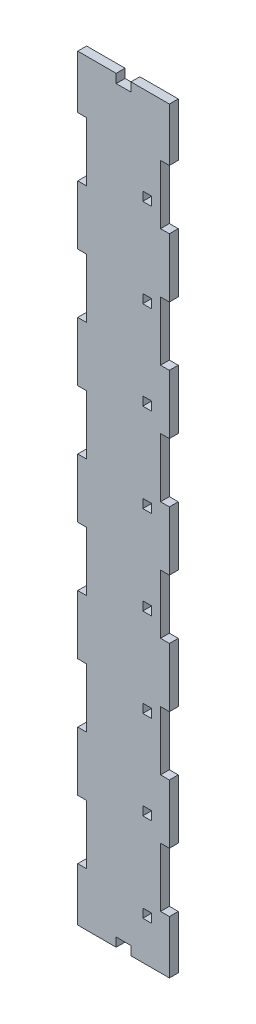
SolidWorks part; units mm, degrees
ref_plane "Front Plane" through (0, 0, 0) normal (0, 0, 1) x (1, 0, 0)
ref_plane "Top Plane" through (0, 0, 0) normal (0, 1, 0) x (1, 0, 0)
ref_plane "Right Plane" through (0, 0, 0) normal (1, 0, 0) x (0, 0, -1)
sketch "Эскиз2" plane through (0, 0, 0) normal (0, 0, 1) x (1, 0, 0)
  line L0 (-118.1292, 271.6721) -> (-110.4161, 271.6721)
  line L1 (-110.4161, 271.6721) -> (-110.4161, 276.0661)
  line L2 (-110.4161, 276.0661) -> (-86.722, 276.0661)
  line L3 (-86.722, 276.0661) -> (-86.722, 271.6721)
  line L4 (-86.722, 271.6721) -> (-64.5567, 271.6721)
  line L5 (-64.5567, 271.6721) -> (-64.5567, 276.0661)
  line L6 (-64.5567, 276.0661) -> (-40.8626, 276.0661)
  line L7 (-40.8626, 276.0661) -> (-40.8626, 271.6721)
  line L8 (-40.8626, 271.6721) -> (-10.2897, 271.6721)
  line L9 (-10.2897, 271.6721) -> (-10.2897, 248.237)
  line L10 (-10.2897, 248.237) -> (-4.5573, 248.237)
  line L11 (-4.5573, 248.237) -> (-4.5573, 230.0748)
  line L12 (-4.5573, 230.0748) -> (-10.2897, 230.0748)
  line L13 (-10.2897, 230.0748) -> (-10.2897, 213.0843)
  line L14 (-10.2897, 213.0843) -> (-4.5573, 213.0843)
  line L15 (-4.5573, 213.0843) -> (-4.5573, 194.9221)
  line L16 (-4.5573, 194.9221) -> (-10.2897, 194.9221)
  line L17 (-10.2897, 194.9221) -> (-10.2897, 177.9317)
  line L18 (-10.2897, 177.9317) -> (-4.5573, 177.9317)
  line L19 (-4.5573, 177.9317) -> (-4.5573, 159.7695)
  line L20 (-4.5573, 159.7695) -> (-10.2897, 159.7695)
  line L21 (-10.2897, 159.7695) -> (-10.2897, 142.7791)
  line L22 (-10.2897, 142.7791) -> (-4.5573, 142.7791)
  line L23 (-4.5573, 142.7791) -> (-4.5573, 124.6169)
  line L24 (-4.5573, 124.6169) -> (-10.2897, 124.6169)
  line L25 (-10.2897, 124.6169) -> (-10.2897, 107.6264)
  line L26 (-10.2897, 107.6264) -> (-4.5573, 107.6264)
  line L27 (-4.5573, 107.6264) -> (-4.5573, 89.4642)
  line L28 (-4.5573, 89.4642) -> (-10.2897, 89.4642)
  line L29 (-10.2897, 89.4642) -> (-10.2897, 72.4738)
  line L30 (-10.2897, 72.4738) -> (-4.5573, 72.4738)
  line L31 (-4.5573, 72.4738) -> (-4.5573, 54.3116)
  line L32 (-4.5573, 54.3116) -> (-10.2897, 54.3116)
  line L33 (-10.2897, 21.59) -> (-41.4508, 21.59)
  line L34 (-41.4508, 21.59) -> (-41.4508, 17.1959)
  line L35 (-41.4508, 17.1959) -> (-65.1449, 17.1959)
  line L36 (-65.1449, 17.1959) -> (-65.1449, 21.59)
  line L37 (-65.1449, 21.59) -> (-87.3102, 21.59)
  line L38 (-87.3102, 21.59) -> (-87.3102, 17.1959)
  line L39 (-87.3102, 17.1959) -> (-111.0043, 17.1959)
  line L40 (-111.0043, 17.1959) -> (-111.0043, 21.59)
  line L41 (-111.0043, 21.59) -> (-118.7174, 21.59)
  line L42 (-118.7174, 21.59) -> (-133.1696, 21.59)
  line L43 (-133.1696, 21.59) -> (-133.1696, 17.1959)
  line L44 (-133.1696, 17.1959) -> (-156.8637, 17.1959)
  line L45 (-156.8637, 17.1959) -> (-156.8637, 21.59)
  line L46 (-156.8637, 21.59) -> (-179.029, 21.59)
  line L47 (-179.029, 21.59) -> (-179.029, 17.1959)
  line L48 (-179.029, 17.1959) -> (-202.7231, 17.1959)
  line L49 (-202.7231, 17.1959) -> (-202.7231, 21.59)
  line L50 (-202.7231, 21.59) -> (-224.8885, 21.59)
  line L51 (-224.8885, 21.59) -> (-224.8885, 17.1959)
  line L52 (-224.8885, 17.1959) -> (-248.5825, 17.1959)
  line L53 (-248.5825, 17.1959) -> (-248.5825, 21.59)
  line L54 (-248.5825, 21.59) -> (-270.7479, 21.59)
  line L55 (-270.7479, 21.59) -> (-270.7479, 17.1959)
  line L56 (-270.7479, 17.1959) -> (-294.4419, 17.1959)
  line L57 (-294.4419, 17.1959) -> (-294.4419, 21.59)
  line L58 (-294.4419, 21.59) -> (-316.6073, 21.59)
  line L59 (-316.6073, 21.59) -> (-316.6073, 17.1959)
  line L60 (-316.6073, 17.1959) -> (-340.3013, 17.1959)
  line L61 (-340.3013, 17.1959) -> (-340.3013, 21.59)
  line L62 (-340.3013, 21.59) -> (-370.286, 21.59)
  line L63 (-370.286, 21.59) -> (-370.286, 54.3116)
  line L64 (-370.286, 54.3116) -> (-376.0185, 54.3116)
  line L65 (-376.0185, 54.3116) -> (-376.0185, 72.4738)
  line L66 (-376.0185, 72.4738) -> (-370.286, 72.4738)
  line L67 (-370.286, 72.4738) -> (-370.286, 89.4642)
  line L68 (-370.286, 89.4642) -> (-376.0185, 89.4642)
  line L69 (-376.0185, 89.4642) -> (-376.0185, 107.6264)
  line L70 (-376.0185, 107.6264) -> (-370.286, 107.6264)
  line L71 (-370.286, 107.6264) -> (-370.286, 124.6169)
  line L72 (-370.286, 124.6169) -> (-376.0185, 124.6169)
  line L73 (-376.0185, 124.6169) -> (-376.0185, 142.7791)
  line L74 (-376.0185, 142.7791) -> (-370.286, 142.7791)
  line L75 (-370.286, 142.7791) -> (-370.286, 159.7695)
  line L76 (-370.286, 159.7695) -> (-376.0185, 159.7695)
  line L77 (-376.0185, 159.7695) -> (-376.0185, 177.9317)
  line L78 (-376.0185, 177.9317) -> (-370.286, 177.9317)
  line L79 (-370.286, 177.9317) -> (-370.286, 194.9221)
  line L80 (-370.286, 194.9221) -> (-376.0185, 194.9221)
  line L81 (-376.0185, 194.9221) -> (-376.0185, 213.0843)
  line L82 (-376.0185, 213.0843) -> (-370.286, 213.0843)
  line L83 (-370.286, 213.0843) -> (-370.286, 230.0748)
  line L84 (-370.286, 230.0748) -> (-376.0185, 230.0748)
  line L85 (-376.0185, 230.0748) -> (-376.0185, 248.237)
  line L86 (-376.0185, 248.237) -> (-370.286, 248.237)
  line L87 (-370.286, 248.237) -> (-370.286, 271.6721)
  line L88 (-370.286, 271.6721) -> (-339.7131, 271.6721)
  line L89 (-339.7131, 271.6721) -> (-339.7131, 276.0661)
  line L90 (-339.7131, 276.0661) -> (-316.0191, 276.0661)
  line L91 (-316.0191, 276.0661) -> (-316.0191, 271.6721)
  line L92 (-316.0191, 271.6721) -> (-293.8537, 271.6721)
  line L93 (-293.8537, 271.6721) -> (-293.8537, 276.0661)
  line L94 (-293.8537, 276.0661) -> (-270.1597, 276.0661)
  line L95 (-270.1597, 276.0661) -> (-270.1597, 271.6721)
  line L96 (-270.1597, 271.6721) -> (-247.9943, 271.6721)
  line L97 (-247.9943, 271.6721) -> (-247.9943, 276.0661)
  line L98 (-247.9943, 276.0661) -> (-224.3003, 276.0661)
  line L99 (-224.3003, 276.0661) -> (-224.3003, 271.6721)
  line L100 (-224.3003, 271.6721) -> (-202.1349, 271.6721)
  line L101 (-202.1349, 271.6721) -> (-202.1349, 276.0661)
  line L102 (-202.1349, 276.0661) -> (-178.4408, 276.0661)
  line L103 (-178.4408, 276.0661) -> (-178.4408, 271.6721)
  line L104 (-178.4408, 271.6721) -> (-156.2755, 271.6721)
  line L105 (-156.2755, 271.6721) -> (-156.2755, 276.0661)
  line L106 (-156.2755, 276.0661) -> (-132.5814, 276.0661)
  line L107 (-132.5814, 276.0661) -> (-132.5814, 271.6721)
  line L108 (-132.5814, 271.6721) -> (-118.1292, 271.6721)
  line L109 (-373.2759, 10.3396) -> (-342.8312, 10.3396)
  line L110 (-342.8312, 10.3396) -> (-342.8312, 6.0284)
  line L111 (-342.8312, 6.0284) -> (-318.4281, 6.0284)
  line L112 (-318.4281, 6.0284) -> (-318.4281, 10.3396)
  line L113 (-318.4281, 10.3396) -> (-296.972, 10.3396)
  line L114 (-296.972, 10.3396) -> (-296.972, 6.0284)
  line L115 (-296.972, 6.0284) -> (-272.5865, 6.0284)
  line L116 (-272.5865, 6.0284) -> (-272.5865, 10.3396)
  line L117 (-272.5865, 10.3396) -> (-251.1875, 10.3396)
  line L118 (-251.1875, 10.3396) -> (-251.1875, 6.0284)
  line L119 (-251.1875, 6.0284) -> (-226.6927, 6.0284)
  line L120 (-226.6927, 6.0284) -> (-226.6927, 10.3396)
  line L121 (-226.6927, 10.3396) -> (-205.259, 10.3396)
  line L122 (-205.259, 10.3396) -> (-205.259, 6.0284)
  line L123 (-205.259, 6.0284) -> (-180.8925, 6.0284)
  line L124 (-180.8925, 6.0284) -> (-180.8925, 10.3396)
  line L125 (-180.8925, 10.3396) -> (-159.5195, 10.3396)
  line L126 (-159.5195, 10.3396) -> (-159.5195, 6.0284)
  line L127 (-159.5195, 6.0284) -> (-135.0267, 6.0284)
  line L128 (-135.0267, 6.0284) -> (-135.0267, 10.3396)
  line L129 (-135.0267, 10.3396) -> (-113.5788, 10.3396)
  line L130 (-113.5788, 10.3396) -> (-113.5788, 6.0284)
  line L131 (-113.5788, 6.0284) -> (-89.2114, 6.0284)
  line L132 (-89.2114, 6.0284) -> (-89.2114, 10.3396)
  line L133 (-89.2114, 10.3396) -> (-67.739, 10.3396)
  line L134 (-67.739, 10.3396) -> (-67.739, 6.0284)
  line L135 (-67.739, 6.0284) -> (-43.1804, 6.0284)
  line L136 (-43.1804, 6.0284) -> (-43.1804, 10.3396)
  line L137 (-43.1804, 10.3396) -> (-12.8557, 10.3396)
  line L138 (-12.8557, 10.3396) -> (-12.8557, -1.3472)
  line L139 (-12.8557, -1.3472) -> (-4.8129, -1.3472)
  line L140 (-4.8129, -1.3472) -> (-4.8194, -8.2165)
  line L141 (-4.8194, -8.2165) -> (-12.8557, -8.2165)
  line L142 (-12.8557, -8.2165) -> (-12.8557, -21.1423)
  line L143 (-12.8557, -21.1423) -> (-43.1804, -21.1423)
  line L144 (-43.1804, -21.1423) -> (-43.1804, -17.4156)
  line L145 (-43.1804, -17.4156) -> (-67.739, -17.4156)
  line L146 (-67.739, -17.4156) -> (-67.739, -21.1423)
  line L147 (-67.739, -21.1423) -> (-89.2114, -21.1423)
  line L148 (-89.2114, -21.1423) -> (-89.2114, -17.4156)
  line L149 (-89.2114, -17.4156) -> (-113.5788, -17.4156)
  line L150 (-113.5788, -17.4156) -> (-113.5788, -21.1423)
  line L151 (-113.5788, -21.1423) -> (-135.0267, -21.1423)
  line L152 (-135.0267, -21.1423) -> (-135.0267, -17.4156)
  line L153 (-135.0267, -17.4156) -> (-159.5195, -17.4156)
  line L154 (-159.5195, -17.4156) -> (-159.5195, -21.1423)
  line L155 (-159.5195, -21.1423) -> (-180.8925, -21.1423)
  line L156 (-180.8925, -21.1423) -> (-180.8931, -17.4156)
  line L157 (-180.8931, -17.4156) -> (-205.259, -17.4156)
  line L158 (-205.259, -17.4156) -> (-205.259, -21.1423)
  line L159 (-205.259, -21.1423) -> (-226.6927, -21.1423)
  line L160 (-226.6927, -21.1423) -> (-226.6927, -17.4156)
  line L161 (-226.6927, -17.4156) -> (-251.1875, -17.4156)
  line L162 (-251.1875, -17.4156) -> (-251.1875, -21.1423)
  line L163 (-251.1875, -21.1423) -> (-272.5865, -21.1423)
  line L164 (-272.5865, -21.1423) -> (-272.5865, -17.4156)
  line L165 (-272.5865, -17.4156) -> (-296.972, -17.4156)
  line L166 (-296.972, -17.4156) -> (-296.972, -21.1423)
  line L167 (-296.972, -21.1423) -> (-318.4281, -21.1423)
  line L168 (-318.4281, -21.1423) -> (-318.4281, -17.4156)
  line L169 (-318.4281, -17.4156) -> (-342.8312, -17.4156)
  line L170 (-342.8312, -17.4156) -> (-342.8312, -21.1423)
  line L171 (-342.8312, -21.1423) -> (-373.2759, -21.1423)
  line L172 (-373.2759, -21.1423) -> (-373.2759, -8.4164)
  line L173 (-373.2759, -8.4164) -> (-379.9791, -8.4164)
  line L174 (-379.9791, -8.4164) -> (-379.9791, -1.5471)
  line L175 (-379.9791, -1.5471) -> (-373.2759, -1.5471)
  line L176 (-373.2759, -1.5471) -> (-373.2759, 10.3396)
  line L177 (-309.7012, -8.7624) -> (-309.7012, -1.506)
  line L178 (-309.7012, -1.506) -> (-306.8626, -1.506)
  line L179 (-306.8626, -1.506) -> (-306.8626, -8.7624)
  line L180 (-306.8626, -8.7624) -> (-309.7012, -8.7624)
  line L181 (-339.711, -8.7225) -> (-339.711, -1.4885)
  line L182 (-339.711, -1.4885) -> (-336.8724, -1.4885)
  line L183 (-336.8724, -1.4885) -> (-336.8724, -8.7225)
  line L184 (-336.8724, -8.7225) -> (-339.711, -8.7225)
  line L185 (-279.6954, -8.7125) -> (-279.6954, -1.4785)
  line L186 (-279.6954, -1.4785) -> (-276.8568, -1.4785)
  line L187 (-276.8568, -1.4785) -> (-276.8568, -8.7125)
  line L188 (-276.8568, -8.7125) -> (-279.6954, -8.7125)
  line L189 (-249.6976, -8.7086) -> (-249.6976, -1.496)
  line L190 (-249.6976, -1.496) -> (-246.859, -1.496)
  line L191 (-246.859, -1.496) -> (-246.859, -8.7086)
  line L192 (-246.859, -8.7086) -> (-249.6976, -8.7086)
  line L193 (-189.6776, -8.5964) -> (-189.6776, -1.4885)
  line L194 (-189.6776, -1.4885) -> (-186.839, -1.4885)
  line L195 (-186.839, -1.4885) -> (-186.839, -8.5964)
  line L196 (-186.839, -8.5964) -> (-189.6776, -8.5964)
  line L197 (-216.8557, -1.4884) -> (-216.8557, -5.6266)
  line L198 (-216.8557, -5.6266) -> (-216.8557, -8.6615)
  line L199 (-216.8557, -8.6615) -> (-219.6943, -8.6615)
  line L200 (-219.6943, -8.6615) -> (-219.6943, -1.4884)
  line L201 (-219.6943, -1.4884) -> (-216.8557, -1.4884)
  line L202 (-159.6718, -8.4591) -> (-159.6718, -1.4885)
  line L203 (-159.6718, -1.4885) -> (-156.8332, -1.4885)
  line L204 (-156.8332, -1.4885) -> (-156.8332, -8.4591)
  line L205 (-156.8332, -8.4591) -> (-159.6718, -8.4591)
  line L206 (-126.0755, -8.4753) -> (-126.0755, -1.4794)
  line L207 (-126.0755, -1.4794) -> (-123.2266, -1.4794)
  line L208 (-123.2266, -1.4794) -> (-123.2266, -8.4753)
  line L209 (-123.2266, -8.4753) -> (-126.0755, -8.4753)
  line L210 (32.0426, 264.3465) -> (32.0426, 233.4466)
  line L211 (32.0426, 233.4466) -> (26.1557, 233.4466)
  line L212 (26.1557, 233.4466) -> (26.1557, 214.8844)
  line L213 (26.1557, 214.8844) -> (32.0426, 214.8844)
  line L214 (32.0426, 214.8844) -> (32.0426, 198.2939)
  line L215 (32.0426, 198.2939) -> (26.1557, 198.2939)
  line L216 (26.1557, 198.2939) -> (26.1557, 179.5405)
  line L217 (26.1557, 179.5405) -> (32.0426, 179.5405)
  line L218 (32.0426, 179.5405) -> (32.0426, 163.1413)
  line L219 (32.0426, 163.1413) -> (26.1557, 163.1413)
  line L220 (26.1557, 163.1413) -> (26.1557, 144.7791)
  line L221 (26.1557, 144.7791) -> (32.0426, 144.7791)
  line L222 (32.0426, 144.7791) -> (32.0426, 127.9887)
  line L223 (32.0426, 127.9887) -> (26.1557, 127.9887)
  line L224 (26.1557, 127.9887) -> (26.1557, 109.4265)
  line L225 (26.1557, 109.4265) -> (32.0426, 109.4265)
  line L226 (32.0426, 109.4265) -> (32.0426, 92.836)
  line L227 (32.0426, 92.836) -> (26.1557, 92.836)
  line L228 (26.1557, 92.836) -> (26.1557, 74.4738)
  line L229 (26.1557, 74.4738) -> (32.0426, 74.4738)
  line L230 (32.0426, 74.4738) -> (32.0426, 57.4834)
  line L231 (32.0426, 57.4834) -> (26.1557, 57.4834)
  line L232 (26.1557, 57.4834) -> (26.1557, 39.3212)
  line L233 (26.1557, 39.3212) -> (32.0426, 39.3212)
  line L234 (32.0426, 39.3212) -> (32.0426, 29.9952)
  line L235 (32.0426, 29.9952) -> (32.0426, -0.6964)
  line L236 (32.0426, -0.6964) -> (20.0028, -0.6964)
  line L237 (20.0028, -0.6964) -> (20.0028, 6.7202)
  line L238 (20.0028, 6.7202) -> (12.704, 6.7202)
  line L239 (12.704, 6.7202) -> (12.704, -0.6964)
  line L240 (12.704, -0.6964) -> (-0.0144, -0.6964)
  line L241 (-0.0144, 39.3212) -> (6.3507, 39.3212)
  line L242 (6.3507, 39.3212) -> (6.3507, 57.4834)
  line L243 (6.3507, 57.4834) -> (-0.0144, 57.4834)
  line L244 (-0.0144, 57.4834) -> (-0.0144, 74.4738)
  line L245 (-0.0144, 74.4738) -> (6.3507, 74.4738)
  line L246 (6.3507, 74.4738) -> (6.3507, 92.836)
  line L247 (6.3507, 92.836) -> (-0.0144, 92.836)
  line L248 (-0.0144, 92.836) -> (-0.0144, 109.4265)
  line L249 (-0.0144, 109.4265) -> (6.3507, 109.4265)
  line L250 (6.3507, 109.4265) -> (6.3507, 127.9887)
  line L251 (6.3507, 127.9887) -> (-0.0144, 127.9887)
  line L252 (-0.0144, 127.9887) -> (-0.0144, 144.7791)
  line L253 (-0.0144, 144.7791) -> (6.3507, 144.7791)
  line L254 (6.3507, 144.7791) -> (6.3507, 163.1413)
  line L255 (6.3507, 163.1413) -> (-0.0144, 163.1413)
  line L256 (-0.0144, 163.1413) -> (-0.0144, 179.5405)
  line L257 (-0.0144, 179.5405) -> (6.3507, 179.5405)
  line L258 (6.3507, 179.5405) -> (6.3507, 198.2939)
  line L259 (6.3507, 198.2939) -> (-0.0144, 198.2939)
  line L260 (-0.0144, 198.2939) -> (-0.0144, 214.8844)
  line L261 (-0.0144, 214.8844) -> (6.3507, 214.8844)
  line L262 (6.3507, 214.8844) -> (6.3507, 233.4466)
  line L263 (6.3507, 233.4466) -> (-0.0144, 233.4466)
  line L264 (-0.0144, 233.4466) -> (-0.0144, 264.3465)
  line L265 (-0.0144, 264.3465) -> (13.0137, 264.3465)
  line L266 (13.0137, 264.3465) -> (13.0137, 256.7736)
  line L267 (13.0137, 256.7736) -> (19.9331, 256.7736)
  line L268 (19.9331, 256.7736) -> (19.9331, 264.3465)
  line L269 (19.9331, 264.3465) -> (32.0426, 264.3465)
  line L270 (12.6691, 193.1597) -> (19.9255, 193.1597)
  line L271 (19.9255, 193.1597) -> (19.9255, 190.3211)
  line L272 (19.9255, 190.3211) -> (12.6691, 190.3211)
  line L273 (12.6691, 190.3211) -> (12.6691, 193.1597)
  line L274 (12.709, 223.1695) -> (19.943, 223.1695)
  line L275 (19.943, 223.1695) -> (19.943, 220.3309)
  line L276 (19.943, 220.3309) -> (12.709, 220.3309)
  line L277 (12.709, 220.3309) -> (12.709, 223.1695)
  line L278 (12.719, 163.1539) -> (19.953, 163.1539)
  line L279 (19.953, 163.1539) -> (19.953, 160.3153)
  line L280 (19.953, 160.3153) -> (12.719, 160.3153)
  line L281 (12.719, 160.3153) -> (12.719, 163.1539)
  line L282 (12.7229, 133.1561) -> (19.9355, 133.1561)
  line L283 (19.9355, 133.1561) -> (19.9355, 130.3175)
  line L284 (19.9355, 130.3175) -> (12.7229, 130.3175)
  line L285 (12.7229, 130.3175) -> (12.7229, 133.1561)
  line L286 (12.8351, 73.1361) -> (19.943, 73.1361)
  line L287 (19.943, 73.1361) -> (19.943, 70.2975)
  line L288 (19.943, 70.2975) -> (12.8351, 70.2975)
  line L289 (12.8351, 70.2975) -> (12.8351, 73.1361)
  line L290 (19.9431, 100.3142) -> (15.8049, 100.3142)
  line L291 (15.8049, 100.3142) -> (12.77, 100.3142)
  line L292 (12.77, 100.3142) -> (12.77, 103.1528)
  line L293 (12.77, 103.1528) -> (19.9431, 103.1528)
  line L294 (19.9431, 103.1528) -> (19.9431, 100.3142)
  line L295 (12.9724, 43.1303) -> (19.943, 43.1303)
  line L296 (19.943, 43.1303) -> (19.943, 40.2917)
  line L297 (19.943, 40.2917) -> (12.9724, 40.2917)
  line L298 (12.9724, 40.2917) -> (12.9724, 43.1303)
  spline S0 degree 3 poles (-10.2897, 54.3116) (-10.2897, 27.8097) (-10.2897, 51.5005) (-10.2897, 21.59) knots 0.3 0.3 0.3 0.3 0.309091 0.309091 0.309091 0.309091
  spline S1 degree 3 poles (-0.0144, -0.6964) (-0.0144, 12.6428) (-0.0144, 25.982) (-0.0144, 39.3212) knots 0.508197 0.508197 0.508197 0.508197 0.52459 0.52459 0.52459 0.52459
sketch "Sketch2" plane through (0, 0, 0) normal (0, 0, 1) x (1, 0, 0)
  line L0 (12.5, 250) -> (12.5, 0) construction
  line L1 (10, 250) -> (15, 250)
  line L2 (0, 235) -> (0, 215)
  line L3 (10, 0) -> (15, 0)
  line L4 (25, 235) -> (25, 215)
  line L7 (0, 253) -> (10, 253)
  line L8 (10, 250) -> (10, 253)
  line L9 (15, 250) -> (15, 253)
  line L12 (15, 253) -> (25, 253)
  line L14 (25, 253) -> (28, 253)
  line L16 (25, 235) -> (28, 235)
  line L17 (28, 253) -> (28, 235)
  line L18 (25, 215) -> (28, 215)
  line L20 (25, 195) -> (28, 195)
  line L21 (28, 215) -> (28, 195)
  line L22 (25, 175) -> (28, 175)
  line L23 (28, 175) -> (28, 155)
  line L24 (25, 155) -> (28, 155)
  line L26 (25, 135) -> (28, 135)
  line L27 (28, 135) -> (28, 115)
  line L28 (25, 115) -> (28, 115)
  line L30 (25, 95) -> (28, 95)
  line L31 (28, 95) -> (28, 75)
  line L32 (25, 75) -> (28, 75)
  line L34 (25, 55) -> (28, 55)
  line L35 (28, 55) -> (28, 35)
  line L36 (25, 35) -> (28, 35)
  line L37 (0, 125) -> (53.8422, 125) construction
  line L38 (25, 15) -> (28, 15)
  line L39 (28, -3) -> (28, 15)
  line L40 (25, -3) -> (28, -3)
  line L42 (0, -3) -> (10, -3)
  line L43 (10, 0) -> (10, -3)
  line L47 (15, -3) -> (25, -3)
  line L48 (15, 0) -> (15, -3)
  line L49 (25, 35) -> (25, 15)
  line L50 (0, -3) -> (-3, -3)
  line L51 (-3, -3) -> (-3, 15)
  line L52 (0, 15) -> (-3, 15)
  line L54 (0, 55) -> (-3, 55)
  line L55 (-3, 55) -> (-3, 35)
  line L56 (0, 35) -> (-3, 35)
  line L58 (0, 95) -> (-3, 95)
  line L59 (-3, 95) -> (-3, 75)
  line L60 (0, 75) -> (-3, 75)
  line L62 (0, 135) -> (-3, 135)
  line L63 (-3, 135) -> (-3, 115)
  line L64 (0, 115) -> (-3, 115)
  line L66 (0, 175) -> (-3, 175)
  line L67 (-3, 175) -> (-3, 155)
  line L68 (0, 155) -> (-3, 155)
  line L70 (0, 195) -> (-3, 195)
  line L71 (-3, 215) -> (-3, 195)
  line L72 (0, 215) -> (-3, 215)
  line L74 (0, 235) -> (-3, 235)
  line L75 (-3, 253) -> (-3, 235)
  line L76 (0, 253) -> (-3, 253)
  line L78 (25, 250) -> (25, 253) [skipped]
  line L79 (0, 195) -> (0, 175)
  line L80 (25, 195) -> (25, 175)
  line L81 (25, 155) -> (25, 135)
  line L82 (0, 155) -> (0, 135)
  line L83 (0, 115) -> (0, 95)
  line L84 (0, 35) -> (0, 15)
  line L85 (0, 75) -> (0, 55)
  line L86 (25, 75) -> (25, 55)
  line L87 (25, 115) -> (25, 95)
  line L88 (19, 193) -> (19, 190)
  line L89 (19, 223) -> (22, 223)
  line L90 (19, 223) -> (19, 220)
  line L91 (19, 220) -> (22, 220)
  line L92 (22, 223) -> (22, 220)
  line L93 (19, 193) -> (22, 193)
  line L94 (22, 193) -> (22, 190)
  line L95 (19, 190) -> (22, 190)
  line L96 (19, 163) -> (19, 160)
  line L97 (19, 163) -> (22, 163)
  line L98 (22, 163) -> (22, 160)
  line L99 (19, 160) -> (22, 160)
  line L100 (19, 133) -> (19, 130)
  line L101 (19, 133) -> (22, 133)
  line L102 (22, 133) -> (22, 130)
  line L103 (19, 130) -> (22, 130)
  line L104 (19, 103) -> (19, 100)
  line L105 (19, 103) -> (22, 103)
  line L106 (22, 103) -> (22, 100)
  line L107 (19, 100) -> (22, 100)
  line L108 (19, 73) -> (19, 70)
  line L109 (19, 73) -> (22, 73)
  line L110 (22, 73) -> (22, 70)
  line L111 (19, 70) -> (22, 70)
  line L112 (19, 43) -> (19, 40)
  line L113 (19, 43) -> (22, 43)
  line L114 (22, 43) -> (22, 40)
  line L115 (19, 40) -> (22, 40)
  line L117 (19, 13) -> (19, 10)
  line L118 (19, 13) -> (22, 13)
  line L119 (22, 13) -> (22, 10)
  line L120 (19, 10) -> (22, 10)
  point P10 (25, 235)
  point P102 (20.5, 223)
  dimension "D2" = 18
  dimension "D3" = 25
  dimension "D4" = 10
  dimension "D6" = 3
  dimension "D7" = 3
  dimension "D8" = 3
  dimension "D9" = 20
  dimension "D10" = 20
  dimension "D12" = 20
  dimension "D13" = 3
  dimension "D14" = 250
  dimension "D15" = 3
  dimension "D16" = 3
  dimension "D17" = 27
  dimension "D19" = 27
  dimension "D20" = 3
  dimension "D5" = 2
  dimension "D11" = 5
  dimension "D18" = 8
extrude "Boss-Extrude2" add sketch "Sketch2" along normal blind 3 contours L87 L28 L27 L26 L81 L24 L23 L22 L80 L20 L21 L18 L4 L16 L17 L14 L12 L9 L1 L8 L7 L76 L75 L74 L2 L72 L71 L70 L79 L66 L67 L68 L82 L62 L63 L64 L83 L58 L59 L60 L85 L54 L55 L56 L84 L52 L51 L50 L42 L43 L3
